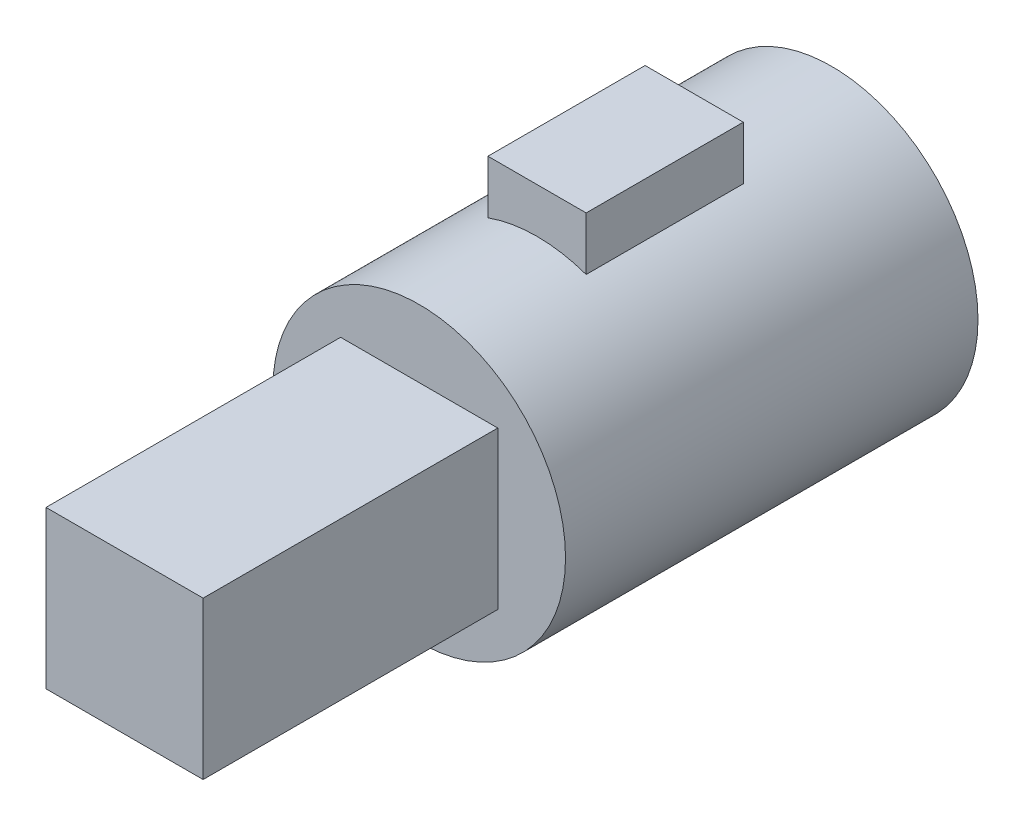
SolidWorks part; units mm, degrees
ref_plane "Front Plane" through (0, 0, 0) normal (0, 0, 1) x (1, 0, 0)
ref_plane "Top Plane" through (0, 0, 0) normal (0, 1, 0) x (1, 0, 0)
ref_plane "Right Plane" through (0, 0, 0) normal (1, 0, 0) x (0, 0, -1)
sketch "Sketch1" plane through (0, 0, 0) normal (0, 0, 1) x (1, 0, 0)
  circle A0 centre (0, 0) radius 7.45
  dimension "D1" = 14.9
extrude "Boss-Extrude1" add sketch "Sketch1" along normal blind 21
sketch "Sketch4" plane through (0, 0, 0) normal (0, 0, -1) x (-1, 0, 0)
  line L1 (2.5, 0) -> (-2.5, 0)
  line L2 (2.5, 0) -> (2.5, 9.7341)
  line L3 (2.5, 9.7341) -> (-2.5, 9.7341)
  line L4 (-2.5, 0) -> (-2.5, 9.7341)
  dimension "D1" = 5
  dimension "D2" = 10.05
extrude "Boss-Extrude4" add sketch "Sketch4" against normal blind 8 from offset 7 offset against normal yes
sketch "Sketch5" plane through (0, 0, 21) normal (0, 0, 1) x (1, 0, 0)
  line L1 (-4, -4) -> (4, -4)
  line L2 (-4, -4) -> (-4, 4)
  line L3 (-4, 4) -> (4, 4)
  line L4 (4, -4) -> (4, 4)
  line L5 (-4, -4) -> (4, 4) construction
  line L6 (-4, 4) -> (4, -4) construction
  point P0 (0, 0)
  dimension "D1" = 8
  dimension "D2" = 8
extrude "Boss-Extrude5" add sketch "Sketch5" along normal blind 15
